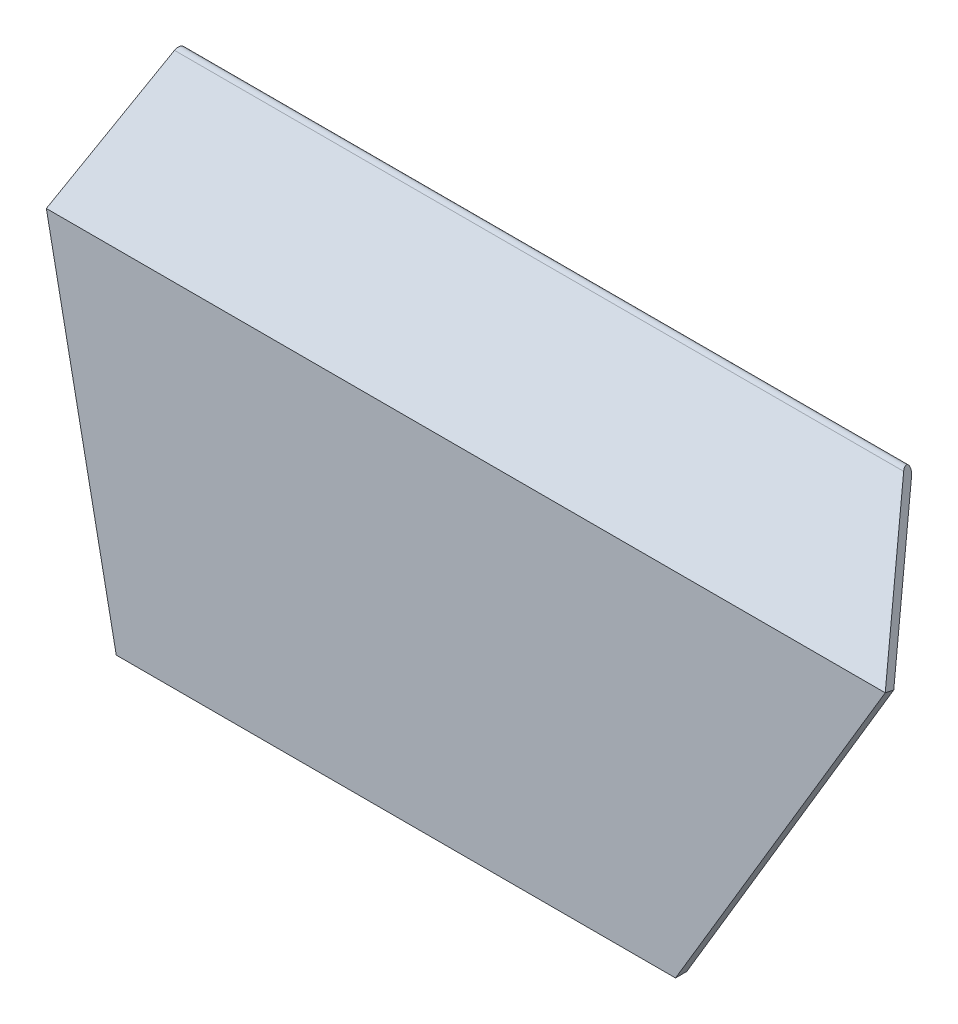
SolidWorks part; units mm, degrees
ref_plane "Front Plane" through (0, 0, 0) normal (0, 0, 1) x (1, 0, 0)
ref_plane "Top Plane" through (0, 0, 0) normal (0, 1, 0) x (1, 0, 0)
ref_plane "Right Plane" through (0, 0, 0) normal (1, 0, 0) x (0, 0, -1)
sketch "Sketch1" plane through (0, 0, 0) normal (1, 0, 0) x (0, 0, -1)
  line L0 (0, 0) -> (0, 500) construction
  line L1 (0, 500) -> (141.4214, 641.4214) construction
  line L2 (8, 0) -> (8, 496.6863)
  line L3 (8, 496.6863) -> (147.0782, 635.7645)
  line L4 (-8, 0) -> (-8, 503.3137)
  line L5 (-8, 503.3137) -> (135.7645, 647.0782)
  line L6 (-8, 0) -> (8, 0)
  arc A1 (147.0782, 635.7645) -> (135.7645, 647.0782) centre (141.4214, 641.4214) ccw
  dimension "D1" = 500
  dimension "D2" = 200
  dimension "D3" = 135
  dimension "D4" = 8
  dimension "D5" = 8
extrude "Boss-Extrude1" add sketch "Sketch1" along normal mid plane 1200
sketch "Sketch2" plane through (0, 0, 8) normal (0, 0, 1) x (1, 0, 0)
  line L1 (600, 0) -> (-600, 0) construction
  line L8 (-600, 503.3137) -> (-500, 0)
  line L9 (-500, 0) -> (-600, 0)
  line L10 (-600, 0) -> (-600, 503.3137)
  line L11 (600, 503.3137) -> (300, 0)
  line L12 (300, 0) -> (600, 0)
  line L13 (600, 0) -> (600, 503.3137)
  dimension "D1" = 100
  dimension "D2" = 300
extrude "Cut-Extrude2" cut sketch "Sketch2" against normal up to surface (16 mm away) up to face at (0, 248.3431, -8)
sketch "Sketch3" plane through (0, 255.6569, 255.6569) normal (0, 0.7071, 0.7071) x (1, 0, 0)
  line L0 (600, 350.2397) -> (477.998, 561.5534)
  line L1 (477.998, 561.5534) -> (600, 561.5534)
  line L2 (600, 561.5534) -> (600, 350.2397)
  line L3 (-600, 350.2397) -> (-558.9248, 561.5534)
  line L4 (-558.9248, 561.5534) -> (-600, 561.5534)
  line L5 (-600, 561.5534) -> (-600, 350.2397)
  dimension "D1" = 11
  dimension "D2" = 30
extrude "Cut-Extrude3" cut sketch "Sketch3" against normal up to surface (16 mm away) up to face at (-0.4389, 543.0457, -54.3594)
sketch "Sketch5" plane through (0, 0, -8) normal (0, 0, -1) x (-1, 0, 0)
  line L0 (176.0787, 333.579) -> (430.6372, 79.0205) construction
  line L1 (176.0787, 79.0205) -> (430.6372, 333.579) construction
  circle A1 centre (430.6372, 333.579) radius 16
  circle A2 centre (176.0787, 333.579) radius 16
  circle A3 centre (176.0787, 79.0205) radius 16
  circle A4 centre (430.6372, 79.0205) radius 16
  point P5 (303.3579, 206.2998)
  point P6 (303.3579, 206.2998)
  point P9 (303.3579, 206.2998)
  dimension "D3" = 32
  dimension "D2" = 360
extrude "Cut-Extrude4" cut sketch "Sketch5" against normal blind 4
